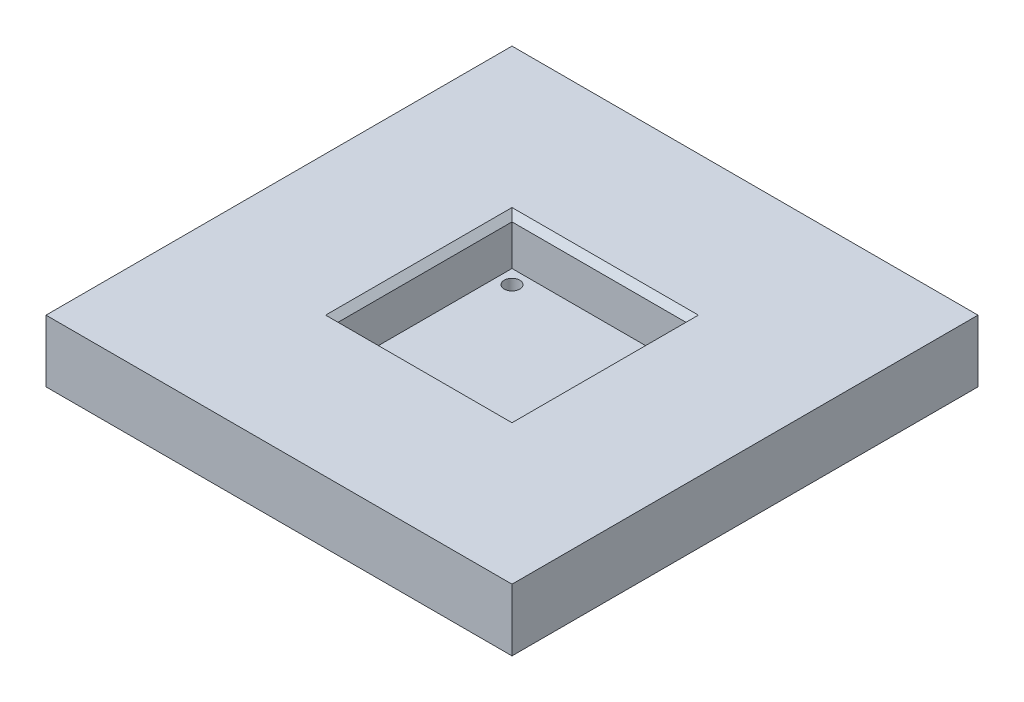
SolidWorks part; units mm, degrees
ref_plane "Piano frontale" through (0, 0, 0) normal (0, 0, 1) x (1, 0, 0)
ref_plane "Piano superiore" through (0, 0, 0) normal (0, 1, 0) x (1, 0, 0)
ref_plane "Piano destro" through (0, 0, 0) normal (1, 0, 0) x (0, 0, -1)
sketch "Schizzo1" plane through (0, 0, 0) normal (0, 1, 0) x (1, 0, 0)
  line L1 (-75, -75) -> (75, -75)
  line L2 (-75, -75) -> (-75, 75)
  line L3 (-75, 75) -> (75, 75)
  line L4 (75, -75) -> (75, 75)
  line L5 (-75, -75) -> (75, 75) construction
  line L6 (-75, 75) -> (75, -75) construction
  point P0 (0, 0)
  dimension "D1" = 150
  dimension "D2" = 150
extrude "Estrusione-Estrusione1" add sketch "Schizzo1" along normal blind 20
sketch "Schizzo2" plane through (0, 20, 0) normal (0, 1, 0) x (1, 0, 0)
  line L1 (-28, -28) -> (28, -28)
  line L2 (-28, -28) -> (-28, 28)
  line L3 (-28, 28) -> (28, 28)
  line L4 (28, -28) -> (28, 28)
  line L5 (-28, -28) -> (28, 28) construction
  line L6 (-28, 28) -> (28, -28) construction
  point P0 (0, 0)
  dimension "D1" = 56
  dimension "D2" = 56
extrude "Taglio-Estrusione1" cut sketch "Schizzo2" against normal blind 15
sketch "Schizzo3" plane through (0, 5, 0) normal (0, 1, 0) x (1, 0, 0)
  line L1 (-23.5, -23.5) -> (23.5, -23.5)
  line L2 (-23.5, -23.5) -> (-23.5, 23.5)
  line L3 (-23.5, 23.5) -> (23.5, 23.5)
  line L4 (23.5, -23.5) -> (23.5, 23.5)
  line L5 (-23.5, -23.5) -> (23.5, 23.5) construction
  line L6 (-23.5, 23.5) -> (23.5, -23.5) construction
  circle A0 centre (23.5, 23.5) radius 2.5
  circle A1 centre (-23.5, 23.5) radius 2.5
  circle A2 centre (-23.5, -23.5) radius 2.5
  circle A3 centre (23.5, -23.5) radius 2.5
  point P0 (0, 0)
  dimension "D3" = 5
  dimension "D4" = 5
  dimension "D5" = 5
  dimension "D6" = 5
  dimension "D1" = 47
  dimension "D2" = 47
extrude "Taglio-Estrusione2" cut sketch "Schizzo3" against normal blind 15 contours A1 | A0 | A3 | A2
chamfer "Smusso1" distance 2 angle 45 4 edges at (-28, 20, 0) (0, 20, 28) (28, 20, 0) (0, 20, -28)
sketch "Schizzo4" plane through (0, 0, 0) normal (0, -1, 0) x (-1, 0, 0)
  line L0 (75, -75) -> (-75, -75) construction
  line L1 (75, 75) -> (75, -75) construction
  circle A0 centre (60, -60) radius 5
  circle A1 centre (-60, -60) radius 5
  circle A2 centre (-60, 60) radius 5
  circle A3 centre (60, 60) radius 5
  circle A4 centre (23.5, -23.5) radius 2.5 construction
  dimension "D1" = 10
  dimension "D2" = 15
  dimension "D3" = 15
  dimension "D4" = 83.5
  dimension "D5" = 83.5
extrude "Taglio-Estrusione3" cut sketch "Schizzo4" against normal blind 15
chamfer "Smusso2" distance 1 angle 45 4 edges at (-60, 0, -55) (60, 0, -65) (60, 0, 65) (-60, 0, 55)
